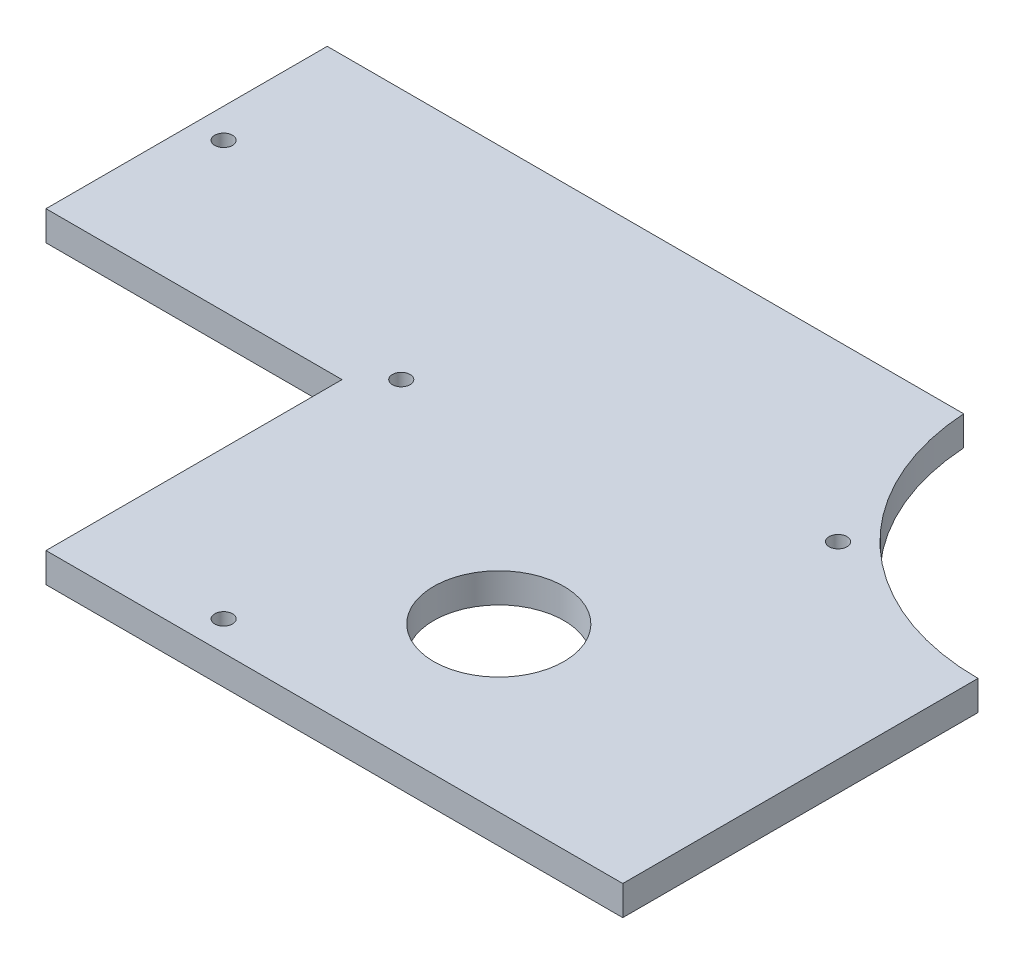
SolidWorks part; units mm, degrees
ref_plane "Plan de face" through (0, 0, 0) normal (0, 0, 1) x (1, 0, 0)
ref_plane "Plan de dessus" through (0, 0, 0) normal (0, 1, 0) x (1, 0, 0)
ref_plane "Plan de droite" through (0, 0, 0) normal (1, 0, 0) x (0, 0, -1)
sketch "Esquisse1" plane through (0, 0, 0) normal (0, 1, 0) x (1, 0, 0)
  line L1 (97.415, -97.415) -> (-97.415, -97.415)
  line L4 (-147.415, -47.415) -> (-147.415, 2.585)
  line L5 (-97.415, -47.415) -> (0, -47.415) construction
  line L6 (-48.7075, -47.415) -> (-48.1634, -92.415) construction
  line L9 (-147.415, 2.585) -> (0, 2.585) construction
  line L14 (-147.415, -47.415) -> (-97.415, -47.415)
  line L15 (-97.415, -47.415) -> (-97.415, -97.415)
  line L16 (-92.415, -92.415) -> (-3.9118, -92.415) construction
  line L17 (-147.415, -42.415) -> (-92.415, -42.415) construction
  line L18 (-92.415, -42.415) -> (-92.415, -97.415) construction
  line L19 (0, 2.585) -> (-31.8198, -29.2348) construction
  line L20 (-147.415, 0.085) -> (-0.1286, 0.085)
  line L21 (0, -97.415) -> (0, 2.585)
  line L27 (-142.415, 2.585) -> (-142.415, -47.415) construction
  circle A3 centre (-142.415, -42.415) radius 1.5 construction
  circle A4 centre (-92.415, -42.415) radius 1.5
  circle A5 centre (-92.415, -92.415) radius 1.5 construction
  circle A14 centre (-142.415, -22.415) radius 1.5
  circle A15 centre (-72.415, -92.415) radius 1.5
  arc A16 (-40, 2.585) -> (0, -37.415) centre (0, 2.585) ccw
  circle A18 centre (-31.8198, -29.2348) radius 1.5
  circle A19 centre (-48.4354, -69.915) radius 11
  point P0 (0, 0)
  dimension "D7" = 20
  dimension "D2" = 3
  dimension "D12" = 40
  dimension "D14" = 22
  dimension "D3" = 45
  dimension "D4" = 5
  dimension "D5" = 5
  dimension "D6" = 5
  dimension "D8" = 20
  dimension "D9" = 5
  dimension "D10" = 50
  dimension "D11" = 194.83
  dimension "D13" = 45
  dimension "D15" = 5
extrude "Boss.-Extru.1" add sketch "Esquisse1" along normal blind 5
